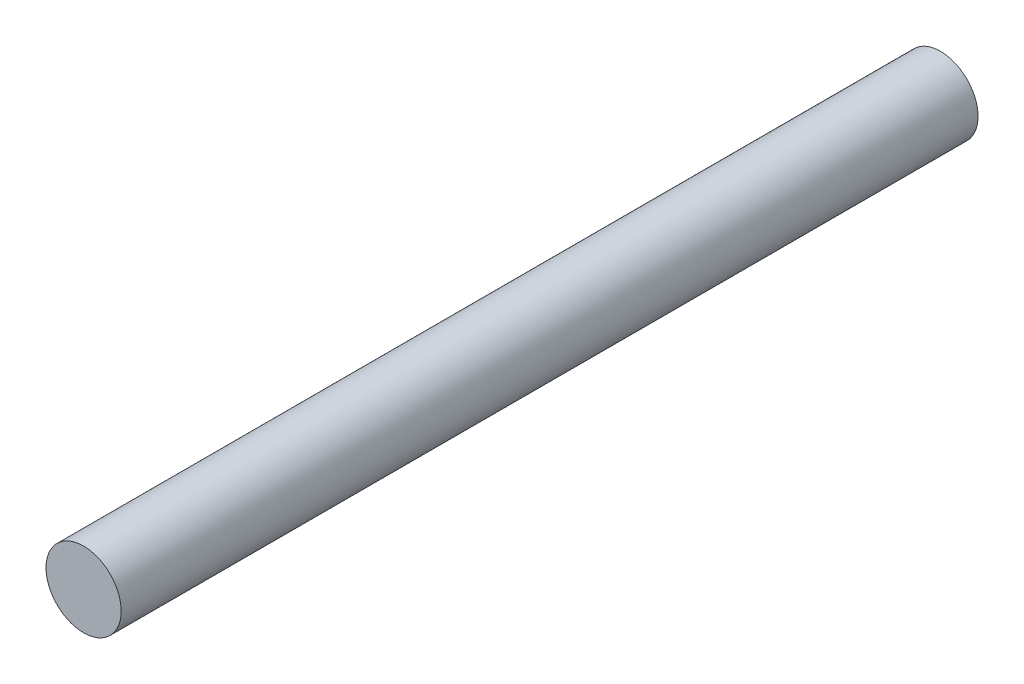
SolidWorks part; units mm, degrees
ref_plane "Спереди" through (0, 0, 0) normal (0, 0, 1) x (1, 0, 0)
ref_plane "Сверху" through (0, 0, 0) normal (0, 1, 0) x (1, 0, 0)
ref_plane "Справа" through (0, 0, 0) normal (1, 0, 0) x (0, 0, -1)
sketch "Эскиз1" plane through (0, 0, 0) normal (0, 0, 1) x (1, 0, 0)
  circle A0 centre (0, 0) radius 2.5
extrude "Вытянуть1" add sketch "Эскиз1" along normal blind 57
